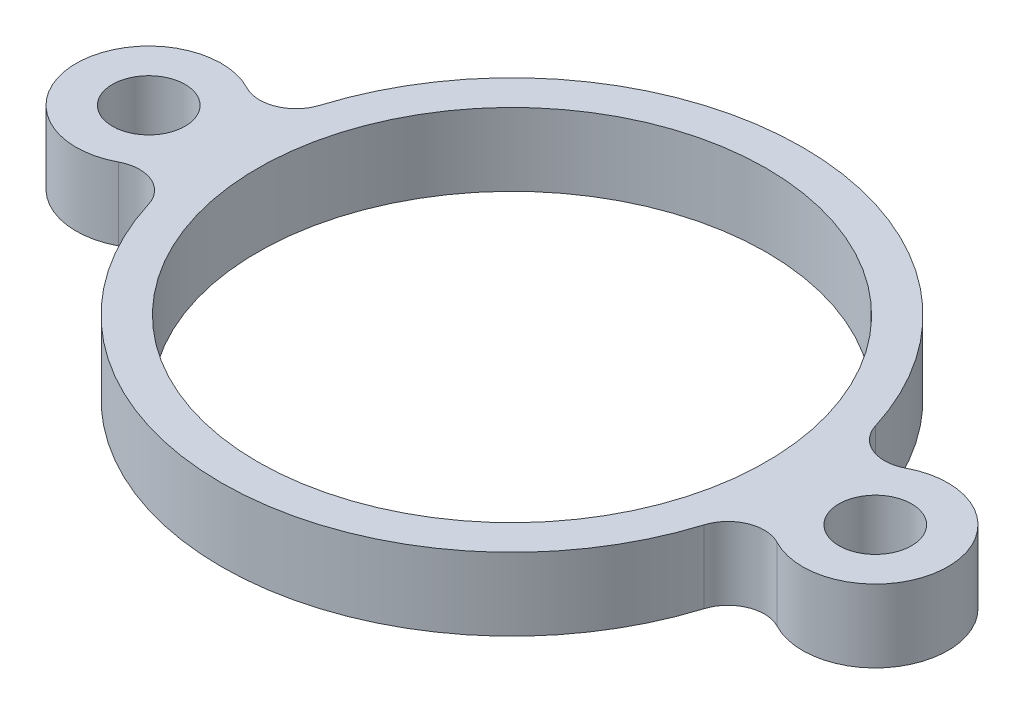
SolidWorks part; units mm, degrees
ref_plane "Front Plane" through (0, 0, 0) normal (0, 0, 1) x (1, 0, 0)
ref_plane "Top Plane" through (0, 0, 0) normal (0, 1, 0) x (1, 0, 0)
ref_plane "Right Plane" through (0, 0, 0) normal (1, 0, 0) x (0, 0, -1)
sketch "Sketch1" plane through (0, 0, 0) normal (0, 1, 0) x (1, 0, 0)
  line L0 (0, 0) -> (50, 0) construction
  line L1 (0, 0) -> (-50, 0) construction
  circle A0 centre (0, 0) radius 35
  circle A1 centre (-50, 0) radius 5
  circle A2 centre (50, 0) radius 5
  arc A3 (-38.2222, -11.7924) -> (38.2222, -11.7924) centre (0, 0) ccw
  arc A4 (-45.3333, 8.8443) -> (-45.3333, -8.8443) centre (-50, 0) ccw
  arc A5 (45.3333, -8.8443) -> (45.3333, 8.8443) centre (50, 0) ccw
  arc A6 (38.2222, 11.7924) -> (-38.2222, 11.7924) centre (0, 0) ccw
  circle A7 centre (-50, 0) radius 10 construction
  circle A8 centre (0, 0) radius 40 construction
  circle A9 centre (50, 0) radius 10 construction
  arc A10 (45.3333, -8.8443) -> (38.2222, -11.7924) centre (43, -13.2665) ccw
  arc A11 (45.3333, 8.8443) -> (38.2222, 11.7924) centre (43, 13.2665) cw
  arc A12 (-45.3333, 8.8443) -> (-38.2222, 11.7924) centre (-43, 13.2665) ccw
  arc A13 (-45.3333, -8.8443) -> (-38.2222, -11.7924) centre (-43, -13.2665) cw
  point P8 (70, 0)
  point P13 (-50, 0)
  point P15 (55, 0)
  point P24 (40, 0)
  dimension "D1" = 70
  dimension "D3" = 10
  dimension "D5" = 5
  dimension "D2" = 50
  dimension "D4" = 5
extrude "Boss-Extrude1" add sketch "Sketch1" along normal blind 10
